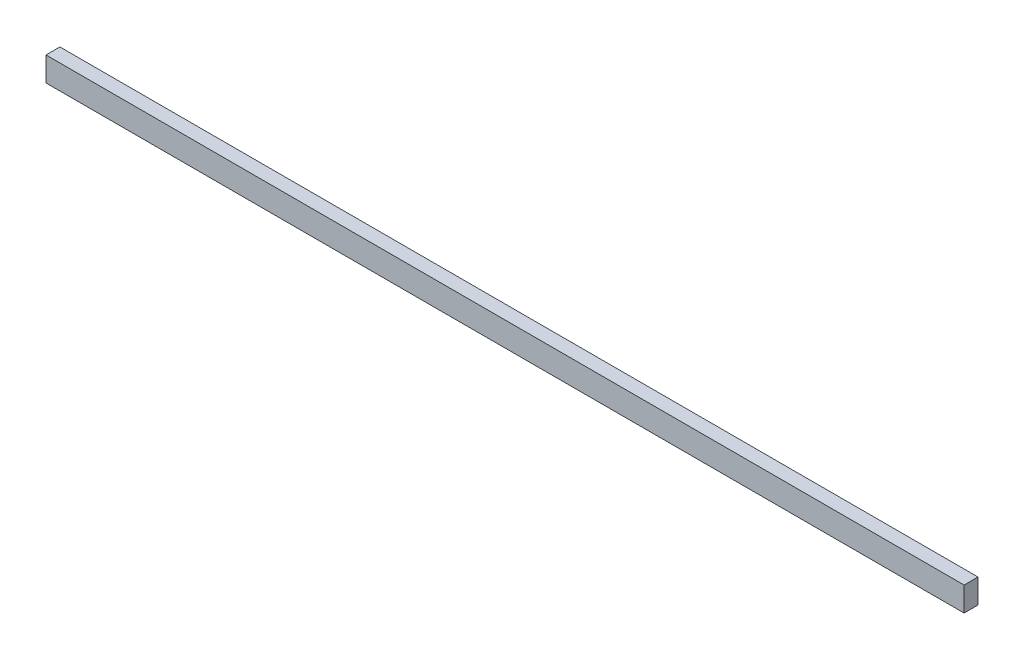
SolidWorks part; units mm, degrees
material "Beech"
ref_plane "Front Plane" through (0, 0, 0) normal (0, 0, 1) x (1, 0, 0)
ref_plane "Top Plane" through (0, 0, 0) normal (0, 1, 0) x (1, 0, 0)
ref_plane "Right Plane" through (0, 0, 0) normal (1, 0, 0) x (0, 0, -1)
sketch "Sketch1" plane through (0, 0, 0) normal (0, 1, 0) x (1, 0, 0)
  line L1 (-224.7215, 5.8228) -> (304.2785, 5.8228)
  line L2 (-224.7215, 5.8228) -> (-224.7215, -2.1772)
  line L3 (-224.7215, -2.1772) -> (304.2785, -2.1772)
  line L4 (304.2785, 5.8228) -> (304.2785, -2.1772)
  dimension "D1" = 8
  dimension "D2" = 529
extrude "Boss-Extrude1" add sketch "Sketch1" along normal blind 14
sketch "Sketch2" plane through (0, 0, 0) normal (0, -1, 0) x (1, 0, 0)
  line L0 (-224.7215, -5.8228) -> (-224.7215, 2.1772) construction
  line L1 (304.2785, -5.8228) -> (-224.7215, -5.8228) construction
  line L2 (304.2785, 2.1772) -> (304.2785, -5.8228) construction
  circle A0 centre (-208.7215, -1.8228) radius 2
  circle A1 centre (288.2785, -1.8228) radius 2
  dimension "D1" = 4
  dimension "D4" = 4
  dimension "D2" = 16
  dimension "D3" = 4
  dimension "D5" = 16
extrude "Cut-Extrude1" cut sketch "Sketch2" against normal blind 10
